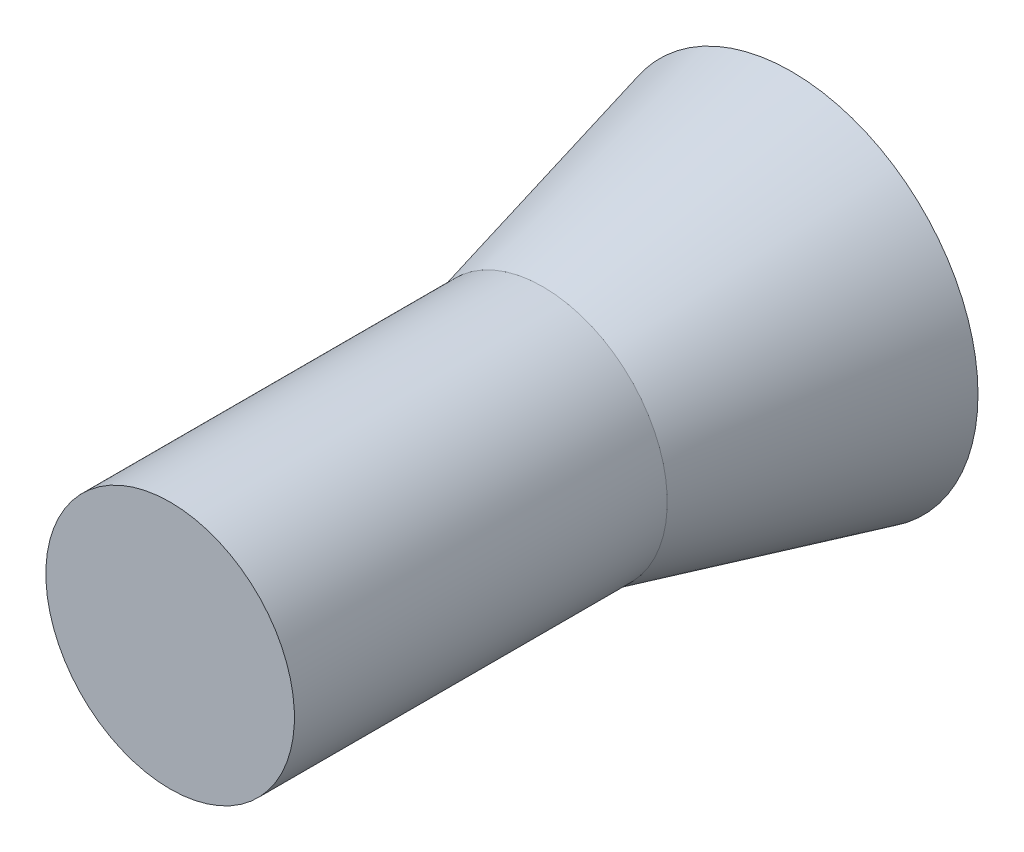
SolidWorks part; units mm, degrees
ref_plane "Front Plane" through (0, 0, 0) normal (0, 0, 1) x (1, 0, 0)
ref_plane "Top Plane" through (0, 0, 0) normal (0, 1, 0) x (1, 0, 0)
ref_plane "Right Plane" through (0, 0, 0) normal (1, 0, 0) x (0, 0, -1)
sketch "Sketch1" plane through (0, 0, 0) normal (1, 0, 0) x (0, 0, -1)
  line L0 (0, 0) -> (-50, 0)
  line L1 (-50, 0) -> (-50, 10)
  line L2 (-50, 10) -> (-20, 10)
  line L3 (-20, 10) -> (0, 15)
  line L4 (0, 15) -> (0, 0)
  dimension "D1" = 15
  dimension "D2" = 10
  dimension "D3" = 20
  dimension "D4" = 30
revolve "Revolve1" add sketch "Sketch1" angle 360 about L0
